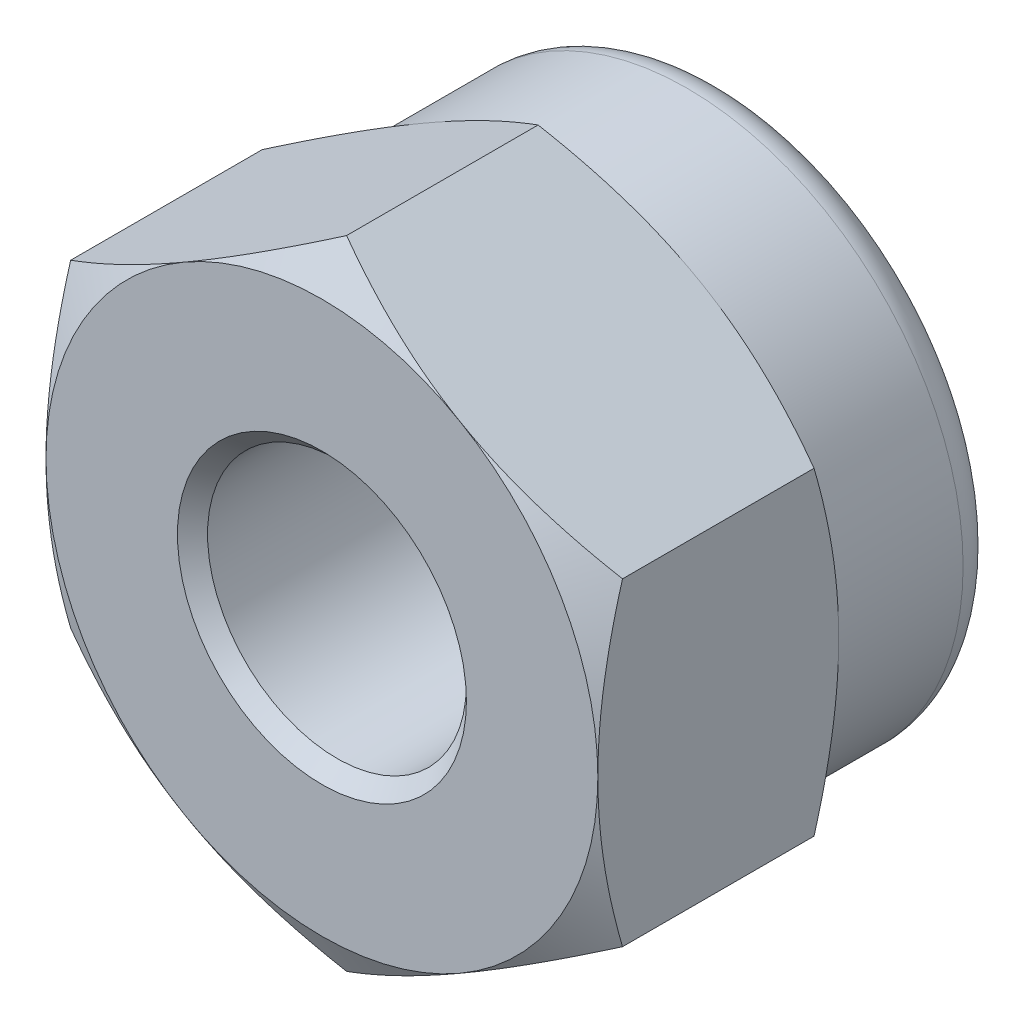
SolidWorks part; units mm, degrees
ref_plane "前视基准面" through (0, 0, 0) normal (0, 0, 1) x (1, 0, 0)
ref_plane "上视基准面" through (0, 0, 0) normal (0, 1, 0) x (1, 0, 0)
ref_plane "右视基准面" through (0, 0, 0) normal (1, 0, 0) x (0, 0, -1)
sketch "草图1" plane through (0, 0, 0) normal (0, 0, 1) x (1, 0, 0)
  line L1 (0, 3.1754) -> (-2.75, 1.5877)
  line L2 (-2.75, 1.5877) -> (-2.75, -1.5877)
  line L3 (-2.75, -1.5877) -> (0, -3.1754)
  line L4 (0, -3.1754) -> (2.75, -1.5877)
  line L5 (2.75, -1.5877) -> (2.75, 1.5877)
  line L6 (2.75, 1.5877) -> (0, 3.1754)
  circle A0 centre (0, 0) radius 2.75 construction
  circle A1 centre (0, 0) radius 1.29
  dimension "D1" = 2.58
  dimension "D2" = 5.5
extrude "凸台-拉伸1" add sketch "草图1" against normal blind 2.4
cosmetic thread "装饰螺纹线1" parameters "D1"=2.4, "D2"=3
sketch "草图2" plane through (0, 0, 0) normal (1, 0, 0) x (0, 0, -1)
  line L0 (0, 2.75) -> (0.2456, 3.1754)
  line L1 (0, 1.5877) -> (0, 3.1754) construction
  line L2 (2.4, 3.1754) -> (0, 3.1754) construction
  line L3 (0.2456, 3.1754) -> (0, 3.1754)
  line L4 (0, 3.1754) -> (0, 2.75)
  line L5 (0, 0) -> (2.4, 0) construction
  line L6 (2.4, -1.5877) -> (2.4, 1.5877) construction
  line L7 (2.4, 2.75) -> (2.1544, 3.1754)
  line L8 (2.4, 1.5877) -> (2.4, 3.1754) construction
  line L9 (2.1544, 3.1754) -> (2.4, 3.1754)
  line L10 (2.4, 3.1754) -> (2.4, 2.75)
  dimension "D1" = 5.5
  dimension "D2" = 30
revolve "切除-旋转1" cut sketch "草图2" angle 360 about L5
chamfer "倒角1" [suppressed] distance 0.15 angle 45
sketch "草图3" [suppressed] plane through (0, 0, 0) normal (0, 0, 1) x (1, 0, 0)
  circle A0 centre (0, 0) radius 2.4
  circle A1 centre (0, 0) radius 3.5
  dimension "D1" = 3.6
extrude "凸台-拉伸2" [suppressed] add sketch "草图3" along normal blind 1.6
fillet "圆角1" [suppressed] radius 0.15
sketch "草图4" [suppressed] plane through (0, 0, 0) normal (0, 0, 1) x (1, 0, 0)
  line L0 (-1.72, 0) -> (-1.9596, 0)
  line L1 (-0.86, 1.4896) -> (-0.9798, 1.6971)
  arc A0 (-1.9596, 0) -> (-2.3515, 0.48) centre (-1.9596, 0.4) cw
  arc A1 (-1.5914, 1.7965) -> (-0.9798, 1.6971) centre (-1.3262, 1.4971) cw
  circle A3 centre (0, 0) radius 2.4 construction
  arc A4 (-1.5914, 1.7965) -> (-2.3515, 0.48) centre (0, 0) ccw
  arc A5 (-0.86, 1.4896) -> (-1.72, 0) centre (0, 0) ccw
  point P4 (-2.4, 0)
  dimension "D1" = 2.58
  dimension "D3" = 0.3
  dimension "D2" = 60
extrude "凸台-拉伸3" [suppressed] add sketch "草图4" along normal blind 0.8
pattern_circular "阵列(圆周)1" [suppressed] count 3 over 360
sketch "草图5" plane through (0, 0, -2.4) normal (0, 0, -1) x (-1, 0, 0)
  circle A0 centre (0, 0) radius 2.75
  circle A2 centre (0, 0) radius 1.65
  dimension "D1" = 3.3
extrude "凸台-拉伸4" add sketch "草图5" along normal blind 1.6
fillet "圆角2" radius 0.36 1 edges at (-2.75, 0, -4)
sketch "草图6" plane through (0, 0, -4) normal (0, 0, -1) x (-1, 0, 0)
  circle A0 centre (0, 0) radius 1.875
  dimension "D1" = 3.75
extrude "切除-拉伸1" cut sketch "草图6" against normal blind 0.4
chamfer "倒角2" distance 0.15 angle 45 2 edges at (1.29, 0, 0) (1.29, 0, -2.4)
equation "\"S\"=5.5"
equation "\"M\"=3"
equation "\"H\"=4"
equation "\"m_\"=2.4"
equation "\"D1@草图1\"  = \"M\" * .86"
equation "\"D2@草图1\" = \"S\""
equation "\"D1@凸台-拉伸1\"=\"m_\""
equation "\"D1@草图2\"=\"S\""
equation "\"D1@倒角1\"=\"M\"*.05"
equation "\"D1@草图3\"=\"M\"*1.2"
equation "\"D1@凸台-拉伸2\" = \"H\" - \"m_\""
equation "\"D1@圆角1\"=\"M\"*.05"
equation "\"D1@草图4\"=\"M\" * .86"
equation "\"D2@草图4\"  = \"AN\""
equation "\"D1@阵列(圆周)1\" = 180 / \"AN\""
equation "\"D1@凸台-拉伸3\"= \"H\" *.5- \"m_\"*.5"
equation "\"D2@装饰螺纹线1\"=\"M\""
equation "\"D1@草图5\"=\"M\"*1.1"
equation "\"D1@凸台-拉伸4\"= \"H\" - \"m_\""
equation "\"D1@圆角2\"=\"M\"*.12"
equation "\"D1@草图6\"=\"M\"*1.25"
equation "\"D1@切除-拉伸1\"= \"H\"*.25 - \"m_\"*.25"
equation "\"AN\"=60"
equation "\"D1@装饰螺纹线1\" = \"m_\""
equation "\"D1@倒角2\"=\"M\"*0.05"
equation "\"D3@草图4\"=\"M\"*0.1"
